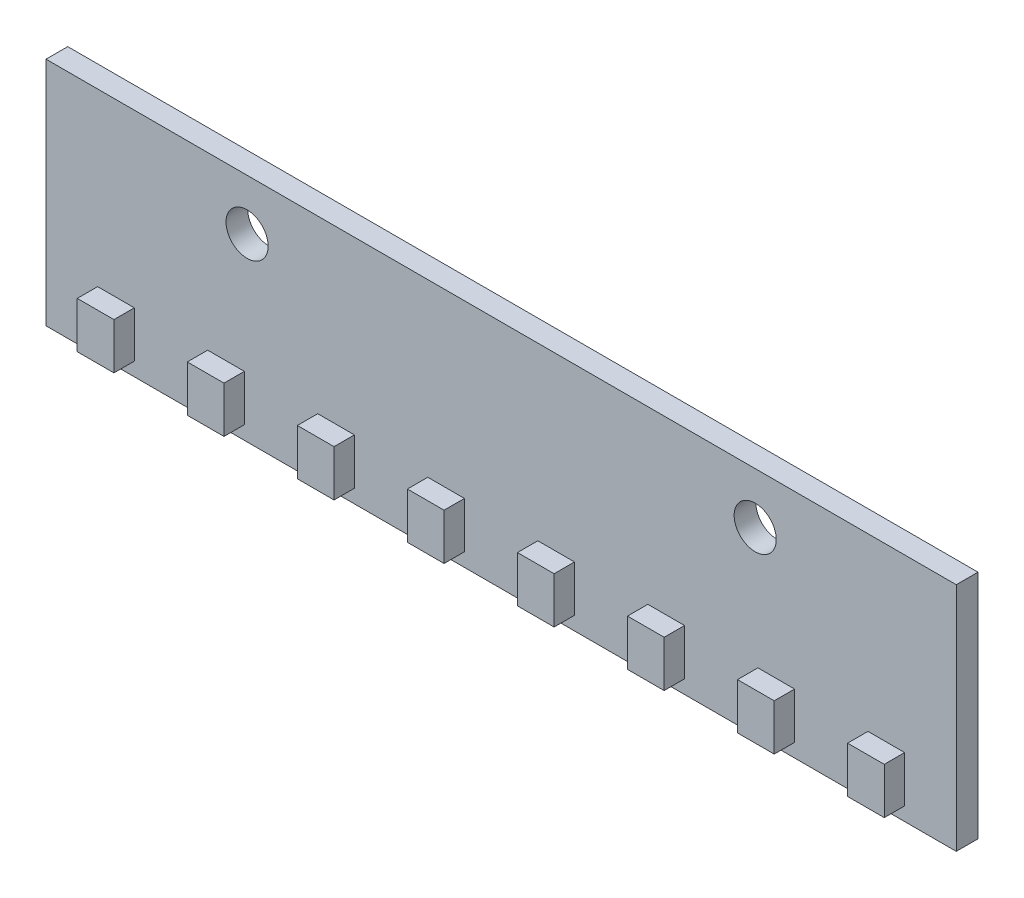
SolidWorks part; units mm, degrees
ref_plane "Plano frontal" through (0, 0, 0) normal (0, 0, 1) x (1, 0, 0)
ref_plane "Plano superior" through (0, 0, 0) normal (0, 1, 0) x (1, 0, 0)
ref_plane "Plano direito" through (0, 0, 0) normal (1, 0, 0) x (0, 0, -1)
sketch "Esboço1" plane through (0, 0, 0) normal (0, 0, 1) x (1, 0, 0)
  line L1 (0, 0) -> (67, 0)
  line L2 (0, 0) -> (0, 17)
  line L3 (0, 17) -> (67, 17)
  line L4 (67, 0) -> (67, 17)
  dimension "D1" = 67
  dimension "D2" = 17
extrude "Ressalto-extrusão1" add sketch "Esboço1" along normal blind 1.6
sketch "Esboço2" plane through (0, 0, 1.6) normal (0, 0, 1) x (1, 0, 0)
  line L0 (14.8, 13.25) -> (0, 13.25) construction
  line L2 (67, 17) -> (0, 17) construction
  line L3 (0, 17) -> (0, 0) construction
  line L4 (52.2, 13.25) -> (67, 13.25) construction
  line L5 (67, 0) -> (67, 17) construction
  circle A0 centre (14.8, 13.25) radius 1.55
  circle A1 centre (52.2, 13.25) radius 1.55
  dimension "D1" = 3.1
  dimension "D2" = 3.75
  dimension "D3" = 37.4
extrude "Corte-extrusão1" cut sketch "Esboço2" against normal through all
sketch "Esboço3" plane through (0, 0, 1.6) normal (0, 0, 1) x (1, 0, 0)
  line L0 (0, 0) -> (67, 0) construction
  line L1 (3.8, 1) -> (6.5, 1)
  line L2 (3.8, 1) -> (3.8, 4.4)
  line L3 (3.8, 4.4) -> (6.5, 4.4)
  line L4 (6.5, 1) -> (6.5, 4.4)
  line L5 (11.9, 1) -> (11.9, 4.4)
  line L6 (11.9, 1) -> (14.6, 1)
  line L7 (14.6, 1) -> (14.6, 4.4)
  line L8 (11.9, 4.4) -> (14.6, 4.4)
  line L9 (20, 1) -> (20, 4.4)
  line L10 (20, 1) -> (22.7, 1)
  line L11 (22.7, 1) -> (22.7, 4.4)
  line L12 (20, 4.4) -> (22.7, 4.4)
  line L13 (28.1, 1) -> (28.1, 4.4)
  line L14 (28.1, 1) -> (30.8, 1)
  line L15 (30.8, 1) -> (30.8, 4.4)
  line L16 (28.1, 4.4) -> (30.8, 4.4)
  line L17 (36.2, 1) -> (36.2, 4.4)
  line L18 (36.2, 1) -> (38.9, 1)
  line L19 (38.9, 1) -> (38.9, 4.4)
  line L20 (36.2, 4.4) -> (38.9, 4.4)
  line L21 (44.3, 1) -> (44.3, 4.4)
  line L22 (44.3, 1) -> (47, 1)
  line L23 (47, 1) -> (47, 4.4)
  line L24 (44.3, 4.4) -> (47, 4.4)
  line L25 (52.4, 1) -> (52.4, 4.4)
  line L26 (52.4, 1) -> (55.1, 1)
  line L27 (55.1, 1) -> (55.1, 4.4)
  line L28 (52.4, 4.4) -> (55.1, 4.4)
  line L29 (60.5, 1) -> (60.5, 4.4)
  line L30 (60.5, 1) -> (63.2, 1)
  line L31 (63.2, 1) -> (63.2, 4.4)
  line L32 (60.5, 4.4) -> (63.2, 4.4)
  line L33 (3.8, 2.7) -> (0, 2.7) construction
  line L34 (0, 17) -> (0, 0) construction
  line L35 (63.2, 2.7) -> (67, 2.7) construction
  line L36 (67, 0) -> (67, 17) construction
  dimension "D1" = 3.4
  dimension "D2" = 2.7
  dimension "D3" = 1
  dimension "D5" = 5.4
  dimension "D4" = 8
extrude "Ressalto-extrusão2" add sketch "Esboço3" along normal blind 1.5
